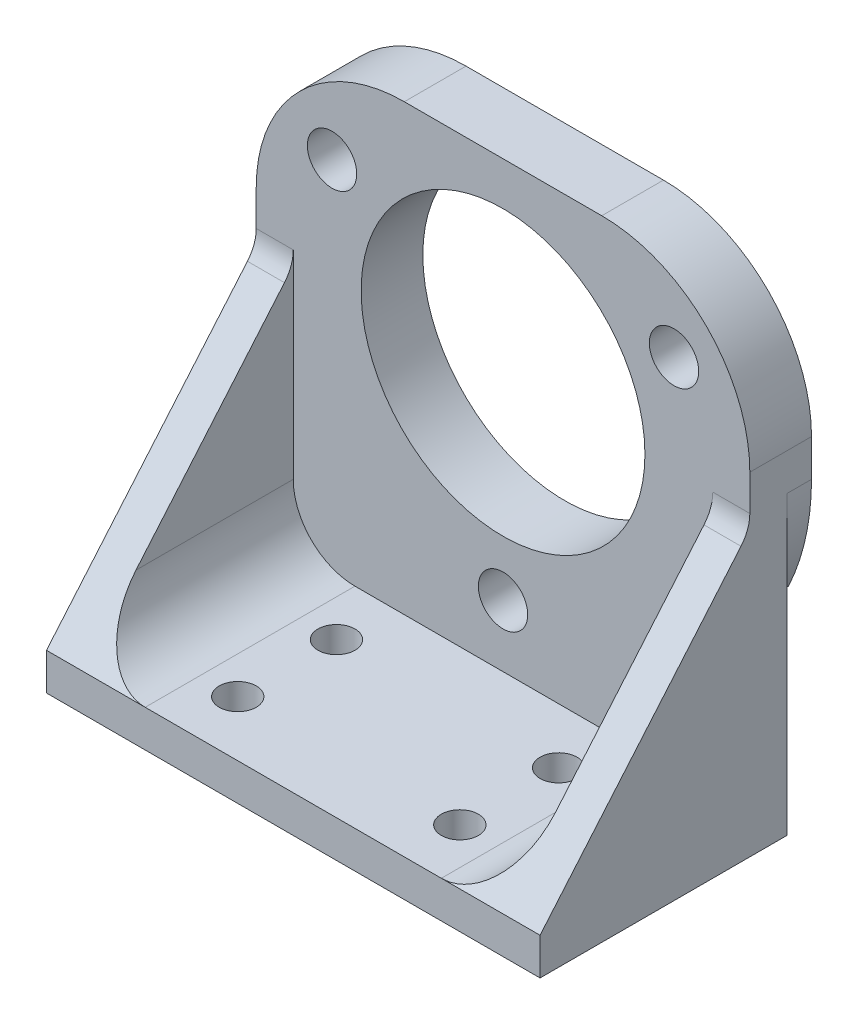
SolidWorks part; units mm, degrees
material "6061 合金"
ref_plane "前视基准面" through (0, 0, 0) normal (0, 0, 1) x (1, 0, 0)
ref_plane "上视基准面" through (0, 0, 0) normal (0, 1, 0) x (1, 0, 0)
ref_plane "右视基准面" through (0, 0, 0) normal (1, 0, 0) x (0, 0, -1)
sketch "草图1" plane through (0, 0, 0) normal (0, 1, 0) x (1, 0, 0)
  line L1 (-20, -10) -> (20, -10)
  line L2 (-20, -10) -> (-20, 10)
  line L3 (-20, 10) -> (20, 10)
  line L4 (20, -10) -> (20, 10)
  line L5 (-20, -10) -> (20, 10) construction
  line L6 (-20, 10) -> (20, -10) construction
  point P0 (0, 0)
  dimension "D1" = 40
  dimension "D2" = 20
extrude "凸台-拉伸1" add sketch "草图1" along normal blind 3
sketch "草图2" plane through (0, 3, 0) normal (0, 1, 0) x (1, 0, 0)
  line L0 (20, -10) -> (20, 10) construction
  line L1 (-20, 10) -> (20, 10)
  line L2 (-20, 10) -> (-20, 7)
  line L3 (-20, 7) -> (20, 7)
  line L4 (20, 10) -> (20, 7)
  dimension "D1" = 3
extrude "凸台-拉伸2" add sketch "草图2" along normal blind 36
sketch "草图3" plane through (0, 0, -7) normal (0, 0, 1) x (1, 0, 0)
  line L0 (0, 0) -> (0, 39) construction
  line L1 (-20, 0) -> (20, 0) construction
  line L2 (-20, 39) -> (20, 39) construction
  line L3 (-20, 3) -> (20, 3) construction
  line L4 (0, 24) -> (13.8564, 32) construction
  circle A0 centre (0, 24) radius 11.5
  circle A2 centre (0, 24) radius 16 construction
  circle A3 centre (13.8564, 32) radius 2
  circle A4 centre (0, 8) radius 2
  circle A5 centre (-13.8564, 32) radius 2
  point P20 (0, 24)
  dimension "D1" = 21
  dimension "D2" = 23
  dimension "D3" = 32
  dimension "D4" = 60
  dimension "D5" = 4
  dimension "D6" = 3
extrude "螺纹-M5" cut sketch "草图3" against normal through all
cosmetic thread "装饰螺纹线1" parameters "D2"=5
cosmetic thread "装饰螺纹线2" parameters "D2"=5
cosmetic thread "装饰螺纹线3" parameters "D2"=5
fillet "圆角1" radius 12 2 edges at (-20, 39, -8.5) (20, 39, -8.5)
sketch "草图4" plane through (0, 0, -10) normal (0, 0, -1) x (-1, 0, 0)
  line L0 (-8, 39) -> (8, 39) construction
  line L1 (-8, 39) -> (8, 39)
  line L2 (20, 27) -> (20, 0) construction
  line L3 (-20, 27) -> (-20, 0) construction
  line L4 (20, 27) -> (20, 24)
  line L5 (-20, 27) -> (-20, 24)
  circle A0 centre (0, 8) radius 2 construction
  circle A1 centre (13.8564, 32) radius 2 construction
  circle A2 centre (-13.8564, 32) radius 2 construction
  circle A3 centre (0, 24) radius 11.5 construction
  circle A4 centre (0, 8) radius 2
  circle A5 centre (13.8564, 32) radius 2
  circle A6 centre (-13.8564, 32) radius 2
  circle A7 centre (0, 24) radius 11.5
  arc A8 (-20, 24) -> (20, 24) centre (0, 24) ccw
  arc A9 (20, 27) -> (8, 39) centre (8, 27) ccw construction
  arc A10 (-8, 39) -> (-20, 27) centre (-8, 27) ccw construction
  arc A11 (20, 27) -> (8, 39) centre (8, 27) ccw
  arc A12 (-8, 39) -> (-20, 27) centre (-8, 27) ccw
  dimension "D1" = 40
extrude "凸台-拉伸3" add sketch "草图4" along normal blind 2
sketch "草图5" plane through (0, 0, -12) normal (0, 0, -1) x (-1, 0, 0)
  line L0 (0, 24) -> (0, 6.5) construction
  line L1 (0, 24) -> (-15.1554, 15.25) construction
  circle A0 centre (0, 24) radius 17.5 construction
  circle A1 centre (-15.1554, 15.25) radius 3
  circle A2 centre (15.1554, 15.25) radius 3
  dimension "D1" = 35
  dimension "D3" = 6
  dimension "D2" = 60
extrude "切除-拉伸2" cut sketch "草图5" against normal blind 2
sketch "草图6" plane through (0, 3, 0) normal (0, 1, 0) x (1, 0, 0)
  line L0 (-20, -10) -> (20, -10) construction
  line L1 (-20, 7) -> (-17, 7)
  line L2 (-20, 7) -> (-20, -10)
  line L3 (-20, -10) -> (-17, -10)
  line L4 (-17, 7) -> (-17, -10)
  line L6 (20, 7) -> (17, 7)
  line L7 (20, 7) -> (20, -10)
  line L8 (20, -10) -> (17, -10)
  line L9 (17, 7) -> (17, -10)
  dimension "D1" = 3
  dimension "D2" = 3
extrude "凸台-拉伸4" add sketch "草图6" along normal blind 20
sketch "草图7" plane through (-20, 0, 0) normal (-1, 0, 0) x (0, 0, 1)
  line L0 (-7, 23) -> (10, 3)
  line L1 (10, 3) -> (10, 23)
  line L2 (10, 23) -> (-7, 23)
extrude "切除-拉伸3" cut sketch "草图7" against normal through all
sketch "草图8" plane through (0, 3, 0) normal (0, 1, 0) x (1, 0, 0)
  line L0 (0, 7) -> (0, -10) construction
  line L1 (-17, -10) -> (17, -10) construction
  line L2 (-9, -5.5) -> (9, -5.5) construction
  line L3 (-9, -5.5) -> (-9, 2.5) construction
  line L4 (17, -10) -> (17, 7)
  line L5 (17, 7) -> (-17, 7)
  line L6 (-17, 7) -> (-17, -10)
  line L7 (-17, -10) -> (17, -10)
  line L8 (17, -10) -> (17, 7) construction
  line L9 (17, 7) -> (-17, 7) construction
  line L10 (-17, 7) -> (-17, -10) construction
  line L11 (-17, -10) -> (17, -10) construction
  line L12 (-9, 2.5) -> (9, 2.5) construction
  line L13 (9, -5.5) -> (9, 2.5) construction
  line L14 (-9, -5.5) -> (9, 2.5) construction
  line L15 (-9, 2.5) -> (9, -5.5) construction
  line L17 (-9, -1.5) -> (9, -1.5) construction
  circle A2 centre (-9, 2.5) radius 1.5
  circle A3 centre (9, 2.5) radius 1.5
  circle A4 centre (9, -5.5) radius 1.5
  circle A5 centre (-9, -5.5) radius 1.5
  point P7 (0, -1.5)
  dimension "D4" = 3
  dimension "D2" = 8
  dimension "D3" = 18
  dimension "D1" = 0
extrude "切除-拉伸4" cut sketch "草图8" against normal through all
fillet "圆角2" radius 5 2 edges at (17, 3, 1.5) (-17, 3, 1.5)
fillet "圆角3" radius 3 2 edges at (18.5, 23, -7) (-18.5, 23, -7)
